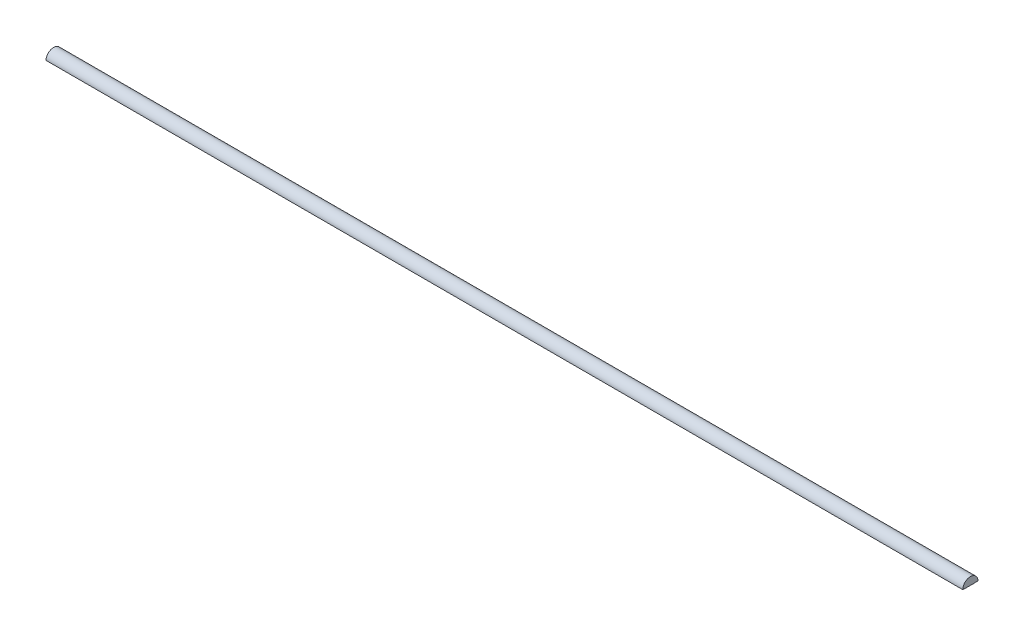
SolidWorks part; units mm, degrees
material "CMR DEFAULT - CHANGE MATERIAL"
ref_plane "XY PLANE - TOP" through (0, 0, 0) normal (0, 0, 1) x (1, 0, 0)
ref_plane "XZ PLANE - SIDE" through (0, 0, 0) normal (0, 1, 0) x (1, 0, 0)
ref_plane "YZ PLANE - FRONT" through (0, 0, 0) normal (1, 0, 0) x (0, 0, -1)
sketch "Sketch1" plane through (0, 0, 0) normal (1, 0, 0) x (0, 0, -1)
  arc A0 (-3.174, -63.4206) -> (3.174, -63.4206) centre (0, 0) ccw
  arc A1 (3.174, -63.4206) -> (-3.174, -63.4206) centre (0, -63.5) ccw
  dimension "D1" = 127
  dimension "D2" = 6.35
extrude "Boss-Extrude1" add sketch "Sketch1" along normal blind 381
